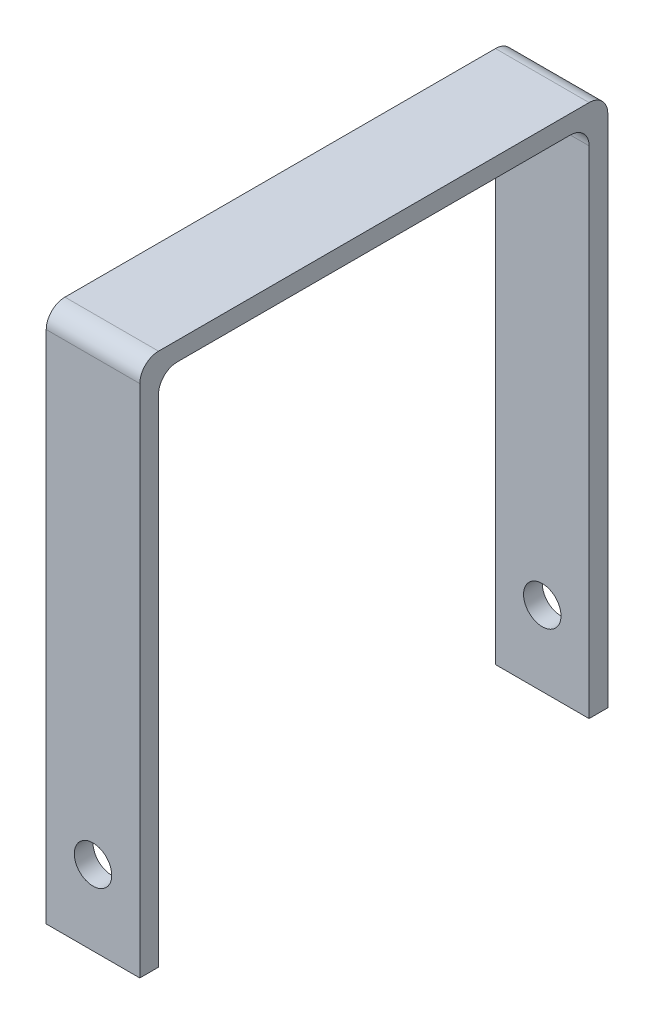
SolidWorks part; units mm, degrees
ref_plane "前视基准面" through (0, 0, 0) normal (0, 0, 1) x (1, 0, 0)
ref_plane "上视基准面" through (0, 0, 0) normal (0, 1, 0) x (1, 0, 0)
ref_plane "右视基准面" through (0, 0, 0) normal (1, 0, 0) x (0, 0, -1)
sketch "草图1" plane through (0, 0, 0) normal (1, 0, 0) x (0, 0, -1)
  line L0 (0, 0) -> (0, 55)
  line L1 (2, 57) -> (48, 57)
  line L2 (25, 57) -> (25, -1.2204) construction
  line L3 (0, 0) -> (2, 0)
  line L4 (2, 0) -> (2, 53)
  line L5 (4, 55) -> (46, 55)
  line L6 (48, 0) -> (48, 53)
  line L7 (50, 0) -> (48, 0)
  line L8 (50, 0) -> (50, 55)
  arc A0 (0, 55) -> (2, 57) centre (2, 55) cw
  arc A1 (2, 53) -> (4, 55) centre (4, 53) cw
  arc A2 (48, 53) -> (46, 55) centre (46, 53) ccw
  arc A3 (50, 55) -> (48, 57) centre (48, 55) ccw
  point P18 (25, 55)
  dimension "D3" = 2
  dimension "D1" = 2
  dimension "D2" = 2
  dimension "D4" = 46
  dimension "D5" = 55
extrude "凸台-拉伸1" add sketch "草图1" along normal blind 10
sketch "草图2" plane through (0, 0, 0) normal (0, 0, 1) x (1, 0, 0)
  line L0 (5, 0) -> (5, 49.2451) construction
  line L1 (10, 0) -> (0, 0) construction
  circle A0 centre (5, 8) radius 2
  dimension "D1" = 4
  dimension "D2" = 8
extrude "切除-拉伸1" cut sketch "草图2" against normal through all
